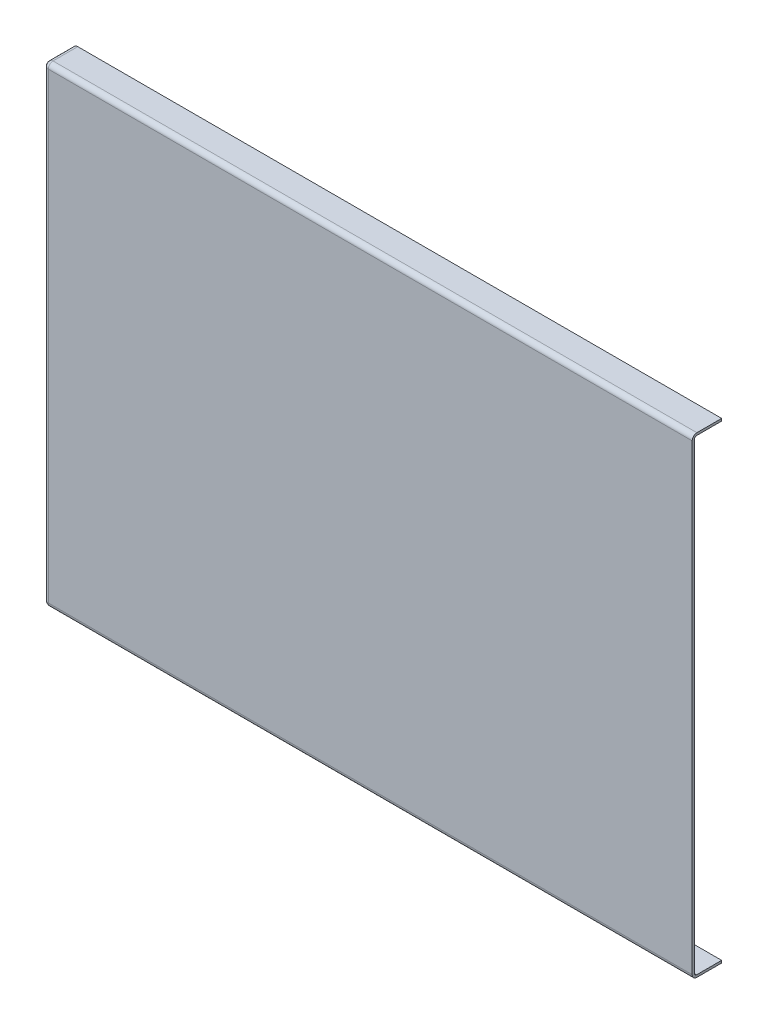
SolidWorks part; units mm, degrees
material "SKD11淬火HRC56-60"
ref_plane "前基準面" through (0, 0, 0) normal (0, 0, 1) x (1, 0, 0)
ref_plane "上基準面" through (0, 0, 0) normal (0, 1, 0) x (1, 0, 0)
ref_plane "右基準面" through (0, 0, 0) normal (1, 0, 0) x (0, 0, -1)
sketch "草图1" plane through (0, 0, 0) normal (0, 0, 1) x (1, 0, 0)
  line L1 (0, 0) -> (550, 0)
  line L2 (0, 0) -> (0, 400)
  line L3 (0, 400) -> (550, 400)
  line L4 (550, 0) -> (550, 400)
  dimension "D1" = 550
  dimension "D2" = 400
extrude "凸台-拉伸1" add sketch "草图1" against normal blind 25
fillet "圆角1" radius 4 5 edges at (275, 400, 0) (0, 400, -12.5) (0, 0, -12.5) (275, 0, 0) (0, 200, 0)
shell "抽壳1" thickness 2
